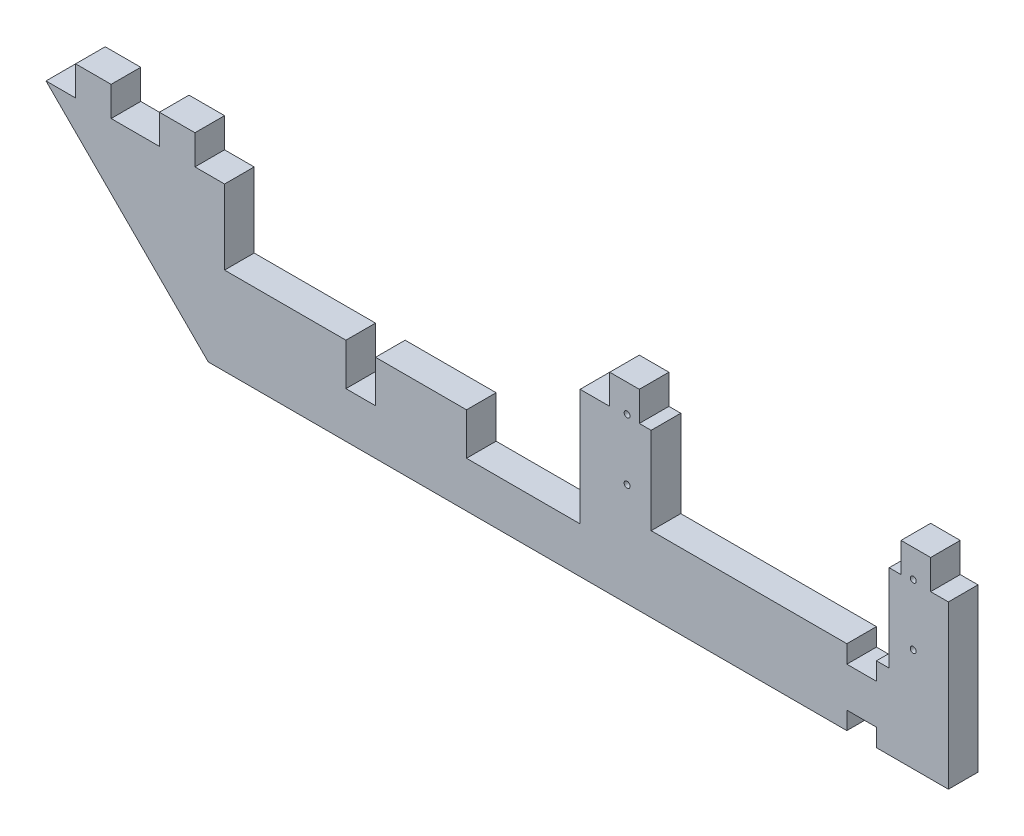
SolidWorks part; units mm, degrees
material "Balsa"
ref_plane "Plan de face" through (0, 0, 0) normal (0, 0, 1) x (1, 0, 0)
ref_plane "Plan de dessus" through (0, 0, 0) normal (0, 1, 0) x (1, 0, 0)
ref_plane "Plan de droite" through (0, 0, 0) normal (1, 0, 0) x (0, 0, -1)
sketch "Esquisse1" plane through (0, 0, 0) normal (0, 0, 1) x (1, 0, 0)
  line L0 (-40.2, 0) -> (-40.2, -19.685)
  line L1 (-40.2, -19.685) -> (0, -19.685)
  line L2 (0, -19.685) -> (0, 0)
  line L3 (0, 0) -> (10, 0)
  line L4 (10, 0) -> (10, -32.4016)
  line L5 (10, -32.4016) -> (-115, -32.4016)
  line L6 (-52.2, -24.685) -> (-52.2, 0)
  line L7 (-52.2, 0) -> (-40.2, 0)
  line L8 (-115, -32.4016) -> (-147.4016, 0)
  line L10 (-71.3842, -17.5925) -> (-71.3842, -24.685)
  line L11 (-71.3842, -24.685) -> (-52.2, -24.685)
  line L12 (-147.4016, 0) -> (-112.247, 0)
  line L13 (-112.247, 0) -> (-112.247, -17.5925)
  line L14 (-112.247, -17.5925) -> (-71.3842, -17.5925)
  dimension "D1" = 19.685
  dimension "D2" = 40.2
  dimension "D3" = 12
  dimension "D4" = 32.4016
  dimension "D5" = 10
  dimension "D6" = 24.685
  dimension "D7" = 17.5925
  dimension "D8" = 72.047
  dimension "D9" = 125
  dimension "D10" = 135
extrude "Boss.-Extru.1" add sketch "Esquisse1" along normal blind 5
sketch "Esquisse2" plane through (0, 0, 0) normal (0, 0, -1) x (-1, 0, 0)
  line L1 (7.15, -19.685) -> (2.15, -19.685)
  line L2 (7.15, -19.685) -> (7.15, -22.685)
  line L3 (7.15, -22.685) -> (2.15, -22.685)
  line L4 (2.15, -19.685) -> (2.15, -22.685)
  line L5 (91.7504, -17.5925) -> (86.7504, -17.5925)
  line L6 (91.7504, -17.5925) -> (91.7504, -24.685)
  line L7 (7.15, -29.4016) -> (2.15, -29.4016)
  line L8 (7.15, -29.4016) -> (7.15, -32.4016)
  line L9 (7.15, -32.4016) -> (2.15, -32.4016)
  line L10 (2.15, -29.4016) -> (2.15, -32.4016)
  line L11 (-10, 0) -> (-7, 0)
  line L12 (-10, 0) -> (-10, -5)
  line L13 (-10, -5) -> (-7, -5)
  line L14 (-7, 0) -> (-7, -5)
  line L15 (52.2, 0) -> (52.2, -24.685) construction
  line L16 (0, 0) -> (-2, 0)
  line L17 (0, 0) -> (0, -5)
  line L18 (0, -5) -> (-2, -5)
  line L19 (-2, 0) -> (-2, -5)
  line L20 (40.2, 0) -> (42.2, 0)
  line L21 (40.2, 0) -> (40.2, -5)
  line L22 (40.2, -5) -> (42.2, -5)
  line L23 (42.2, 0) -> (42.2, -5)
  line L24 (52.2, -5) -> (47.2, -5)
  line L25 (52.2, -5) -> (52.2, 0)
  line L26 (52.2, 0) -> (47.2, 0)
  line L27 (47.2, -5) -> (47.2, 0)
  line L28 (91.7504, -24.685) -> (86.7504, -24.685)
  line L29 (86.7504, -17.5925) -> (86.7504, -24.685)
  line L31 (71.3842, -17.5925) -> (112.247, -17.5925) construction
  line L33 (112.247, -17.5925) -> (112.247, 0) construction
  line L34 (112.247, 0) -> (117.247, 0)
  line L35 (112.247, 0) -> (112.247, -5)
  line L36 (112.247, -5) -> (117.247, -5)
  line L37 (117.247, 0) -> (117.247, -5)
  line L38 (112.247, 0) -> (147.4016, 0) construction
  line L39 (123.247, 0) -> (131.4016, 0)
  line L40 (123.247, 0) -> (123.247, -5)
  line L41 (123.247, -5) -> (131.4016, -5)
  line L42 (131.4016, 0) -> (131.4016, -5)
  line L43 (147.4016, 0) -> (115, -32.4016) construction
  line L44 (137.4016, -5) -> (147.4016, -5)
  line L45 (137.4016, -5) -> (137.4016, 0)
  line L46 (137.4016, 0) -> (147.4016, 0)
  line L47 (147.4016, -5) -> (147.4016, 0)
  dimension "D1" = 19.685
  dimension "D2" = 6.7166
  dimension "D3" = 3
  dimension "D4" = 3
  dimension "D5" = 5
  dimension "D6" = 2.15
  dimension "D7" = 5
  dimension "D8" = 3
  dimension "D9" = 2
  dimension "D10" = 5
  dimension "D11" = 2
  dimension "D12" = 5
  dimension "D13" = 5
  dimension "D14" = 5
  dimension "D15" = 5
  dimension "D16" = 5
  dimension "D17" = 6
  dimension "D18" = 6
  dimension "D19" = 5
  dimension "D20" = 10
extrude "Créneaux -" cut sketch "Esquisse2" against normal blind 5
sketch "Esquisse3" plane through (0, 0, 0) normal (0, 0, -1) x (-1, 0, 0)
  line L0 (-10, -32.4016) -> (-10, -5) construction
  line L1 (-7, 0) -> (-2, 0) construction
  line L2 (40.2, -19.685) -> (40.2, -5) construction
  line L3 (42.2, 0) -> (47.2, 0) construction
  circle A0 centre (-4.064, -14.986) radius 0.5
  circle A1 centre (-4.064, -4.699) radius 0.5
  circle A2 centre (44.264, -14.986) radius 0.5
  circle A3 centre (44.264, -4.699) radius 0.5
  dimension "D1" = 1
  dimension "D2" = 1
  dimension "D7" = 1
  dimension "D8" = 1
  dimension "D3" = 10.287
  dimension "D4" = 5.936
  dimension "D5" = 5.936
  dimension "D6" = 4.699
  dimension "D9" = 4.064
  dimension "D10" = 4.064
  dimension "D11" = 10.287
  dimension "D12" = 4.699
extrude "Perçages" cut sketch "Esquisse3" against normal blind 5
